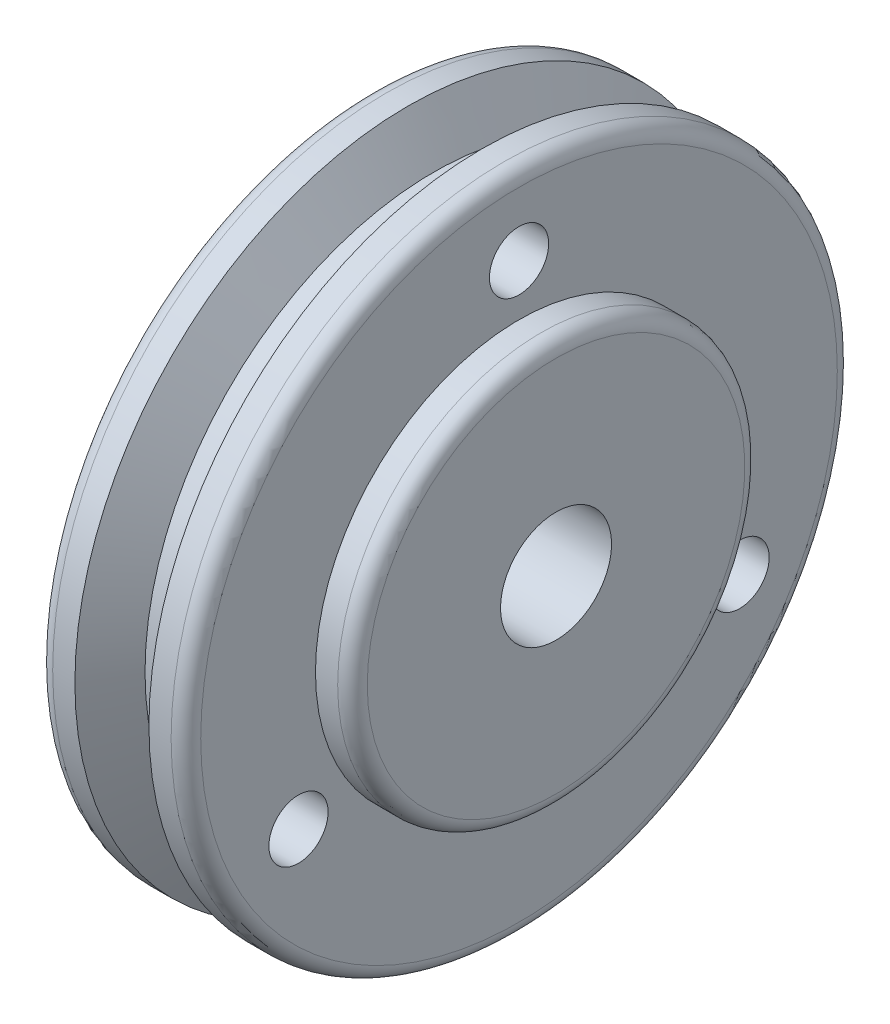
SolidWorks part; units mm, degrees
ref_plane "Ön Düzlem" through (0, 0, 0) normal (0, 0, 1) x (1, 0, 0)
ref_plane "Üst Düzlem" through (0, 0, 0) normal (0, 1, 0) x (1, 0, 0)
ref_plane "Sağ Düzlem" through (0, 0, 0) normal (1, 0, 0) x (0, 0, -1)
sketch "Çizim1" plane through (0, 0, 0) normal (0, 0, 1) x (1, 0, 0)
  line L0 (-1.5009, 45) -> (1.9702, 39)
  line L1 (-20.5009, 17.5) -> (-6.5009, 17.5)
  line L2 (-22.5009, 15.5) -> (-22.5009, 7.5)
  line L3 (-22.5009, 7.5) -> (18.4991, 7.5)
  line L4 (18.4991, 20.0207) -> (18.4991, 7.5)
  line L6 (18.4991, 20.0207) -> (18.4991, 25.5)
  line L7 (16.4991, 27.5) -> (13.4991, 27.5)
  line L8 (-6.5009, 17.5) -> (-6.5009, 24.4421)
  line L10 (-6.5009, 24.4421) -> (-6.5009, 43)
  line L11 (-4.5009, 45) -> (-1.5009, 45)
  line L12 (13.4991, 27.5) -> (13.4991, 43)
  line L13 (1.9702, 39) -> (5.9702, 39)
  line L14 (5.9702, 39) -> (8.4991, 45)
  line L15 (8.4991, 45) -> (11.4991, 45)
  line L16 (-33.8563, 0) -> (47.59, 0) construction
  arc A0 (-20.5009, 17.5) -> (-22.5009, 15.5) centre (-20.5009, 15.5) ccw
  arc A1 (18.4991, 25.5) -> (16.4991, 27.5) centre (16.4991, 25.5) ccw
  arc A2 (11.4991, 45) -> (13.4991, 43) centre (11.4991, 43) cw
  arc A3 (-6.5009, 43) -> (-4.5009, 45) centre (-4.5009, 43) cw
  point P19 (-82.0294, 77.6604)
  point P20 (-22.5009, 17.5)
  point P25 (13.4991, 45)
  point P28 (-6.5009, 45)
  dimension "D11" = 2
  dimension "D1" = 15
  dimension "D2" = 35
  dimension "D3" = 55
  dimension "D4" = 90
  dimension "D5" = 20
  dimension "D6" = 16
  dimension "D7" = 4
  dimension "D8" = 5
  dimension "D9" = 6
  dimension "D10" = 5
  dimension "D12" = 41
revolve "Döndür2" add sketch "Çizim1" angle 360 about L16
sketch "Çizim2" plane through (13.4991, 0, 0) normal (1, 0, 0) x (0, 0, -1)
  circle A0 centre (0, 34.4022) radius 4
  circle A1 centre (29.7932, -17.2011) radius 4
  circle A2 centre (-29.7932, -17.2011) radius 4
  point P10 (0, 0)
  dimension "D1" = 8
  dimension "D2" = 3
extrude "Kes-Ekstrüzyon2" cut sketch "Çizim2" against normal through all
